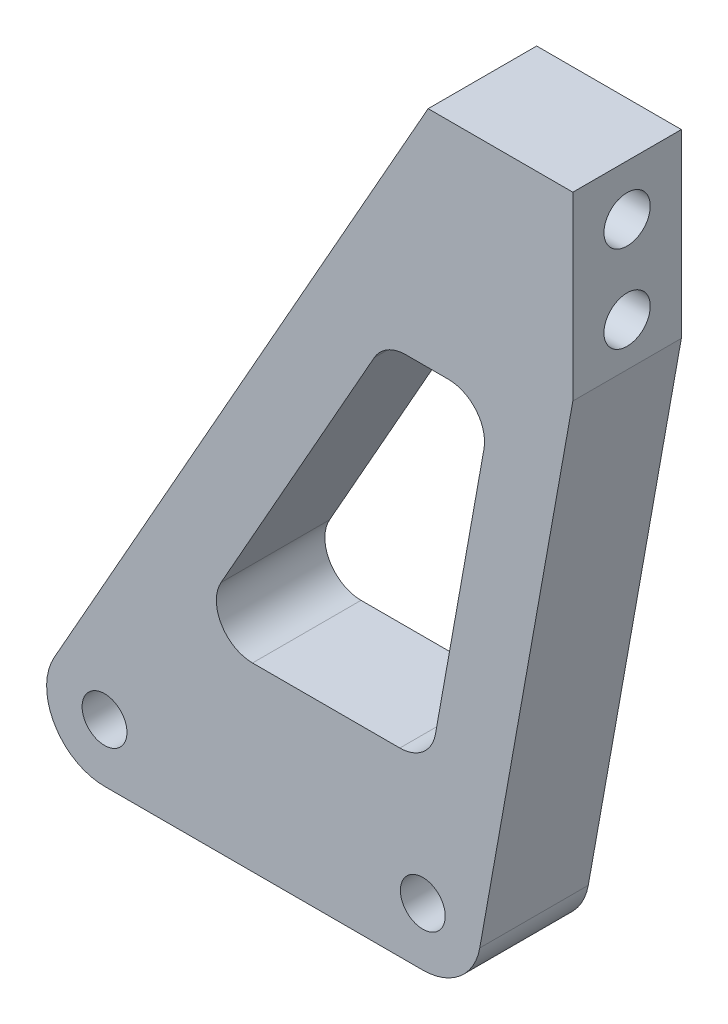
SolidWorks part; units mm, degrees
ref_plane "Front Plane" through (0, 0, 0) normal (0, 0, 1) x (1, 0, 0)
ref_plane "Top Plane" through (0, 0, 0) normal (0, 1, 0) x (1, 0, 0)
ref_plane "Right Plane" through (0, 0, 0) normal (1, 0, 0) x (0, 0, -1)
sketch "Sketch1" plane through (0, 0, 0) normal (0, 0, 1) x (1, 0, 0)
  line L0 (-11, 0) -> (11, 0) construction
  line L1 (-11, 4) -> (11, 4)
  line L2 (-11, -4) -> (11, -4)
  arc A0 (-11, 4) -> (-11, -4) centre (-11, 0) ccw
  arc A1 (11, -4) -> (11, 4) centre (11, 0) ccw
  point P2 (0, 0)
  dimension "D1" = 8
extrude "Boss-Extrude1" add sketch "Sketch1" along normal blind 7.5
sketch "Sketch2" plane through (0, 0, 7.5) normal (0, 0, 1) x (1, 0, 0)
  circle A0 centre (-11, 0) radius 1.55
  arc A2 (-11, 4) -> (-11, -4) centre (-11, 0) ccw construction
  dimension "D1" = 3.1
extrude "Cut-Extrude1" cut sketch "Sketch2" against normal through all contours A0
mirror "Mirror1" about plane through (0, 0, 0) normal (1, 0, 0) of "Cut-Extrude1"
sketch "Sketch12" plane through (0, 0, 7.5) normal (0, 0, 1) x (1, 0, 0)
  line L0 (11, 0) -> (21.37, 0) construction
  line L1 (21.37, 0) -> (21.37, 47.75) construction
  line L2 (21.37, 47.75) -> (11.37, 47.75)
  line L3 (11.37, 47.75) -> (-14.483, 1.9668)
  line L4 (21.37, 47.75) -> (21.37, 35.25)
  line L5 (21.37, 35.25) -> (14.9375, -0.7044)
  line L6 (-11, 4) -> (11, 4) construction
  line L7 (-11, 4) -> (11, 4)
  arc A0 (11, -4) -> (11, 4) centre (11, 0) ccw
  arc A1 (-11, 4) -> (-11, -4) centre (-11, 0) ccw construction
  arc A2 (11, -4) -> (11, 4) centre (11, 0) ccw construction
  arc A3 (-11, 4) -> (-11, -4) centre (-11, 0) ccw
  arc M8 (11, -4) -> (11, 4) centre (11, 0) ccw
  line M9 (11, 4) -> (-11, 4)
  arc M10 (-11, 4) -> (-11, -4) centre (-11, 0) ccw
  dimension "D1" = 10.37
  dimension "D2" = 47.75
  dimension "D3" = 10
  dimension "D4" = 12.5
extrude "Boss-Extrude6" add sketch "Sketch12" against normal up to surface (7.5 mm away) contours L5 L4 L2 L3 M10 M9 M8 up to face at (9.45, 0, 0)
sketch "Sketch13" plane through (21.37, 0, 0) normal (1, 0, 0) x (0, 0, -1)
  circle A0 centre (-3.75, 38.25) radius 1.6 construction
  circle A1 centre (-3.75, 44.25) radius 1.6 construction
  circle A2 centre (-3.75, 38.25) radius 1.6
  circle A3 centre (-3.75, 44.25) radius 1.6
extrude "Cut-Extrude2" cut sketch "Sketch13" against normal up to surface (15.3645 mm away)
sketch "Sketch15" plane through (0, 0, 7.5) normal (0, 0, 1) x (1, 0, 0)
  line L0 (11.37, 47.75) -> (-14.483, 1.9668) construction
  line L6 (15.7539, 32.25) -> (8.3595, 32.25)
  line L7 (-5.0518, 8.5) -> (11.5048, 8.5)
  line L8 (15.7539, 32.25) -> (11.5048, 8.5)
  line L9 (8.3595, 32.25) -> (-5.0518, 8.5)
  line L13 (11.37, 47.75) -> (-13.6173, 3.5) construction
  line L14 (20.6757, 31.3694) -> (15.6897, 3.5) construction
  line L15 (21.37, 35.25) -> (14.9375, -0.7044) construction
  line L16 (-13.6173, 3.5) -> (15.6897, 3.5) construction
  line L17 (-11, -4) -> (11, -4) construction
  line L18 (15.7238, 45.2915) -> (-5.0518, 8.5) construction
  dimension "D1" = 7.5
  dimension "D3" = 10
  dimension "D4" = 3
  dimension "D2" = 5
extrude "Cut-Extrude8" cut sketch "Sketch15" against normal through all contours L8 L7 L9 L6
fillet "Fillet1" radius 2.5 4 edges at (11.5048, 8.5, 3.75) (15.7539, 32.25, 3.75) (8.3595, 32.25, 3.75) (-5.0518, 8.5, 3.75)
